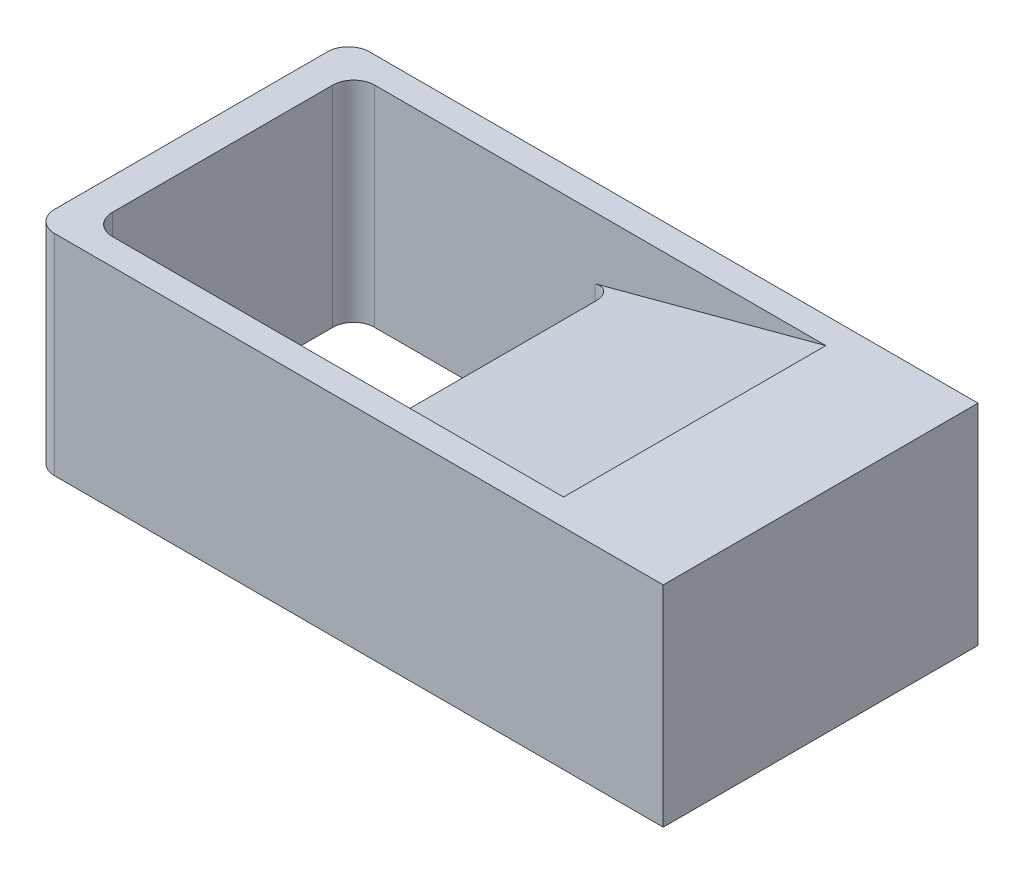
SolidWorks part; units mm, degrees
ref_plane "Alzado" through (0, 0, 0) normal (0, 0, 1) x (1, 0, 0)
ref_plane "Planta" through (0, 0, 0) normal (0, 1, 0) x (1, 0, 0)
ref_plane "Vista lateral" through (0, 0, 0) normal (1, 0, 0) x (0, 0, -1)
sketch "Croquis1" plane through (0, 0, 0) normal (0, 1, 0) x (1, 0, 0)
  line L1 (0, 0) -> (30, 0)
  line L2 (0, 0) -> (0, 15)
  line L3 (0, 15) -> (30, 15)
  line L4 (30, 0) -> (30, 15)
  line L5 (1.5, 13.75) -> (14, 13.75)
  line L6 (1.5, 13.75) -> (1.5, 1.25)
  line L7 (1.5, 1.25) -> (14, 1.25)
  line L8 (14, 13.75) -> (14, 1.25)
  point P9 (1.5, 7.5)
  point P10 (0, 7.5)
  dimension "D1" = 1.5
  dimension "D2" = 12.5
  dimension "D3" = 15
  dimension "D4" = 30
extrude "Saliente-Extruir1" add sketch "Croquis1" along normal blind 10
chamfer "Chaflán1" distance 10 angle 15 1 edges at (14, 10, -7.5)
fillet "Redondeo1" radius 1 6 edges at (0, 5, -15) (0, 5, 0) (1.5, 5, -1.25) (14, 3.6603, -1.25) (14, 3.6603, -13.75) (1.5, 5, -13.75)
